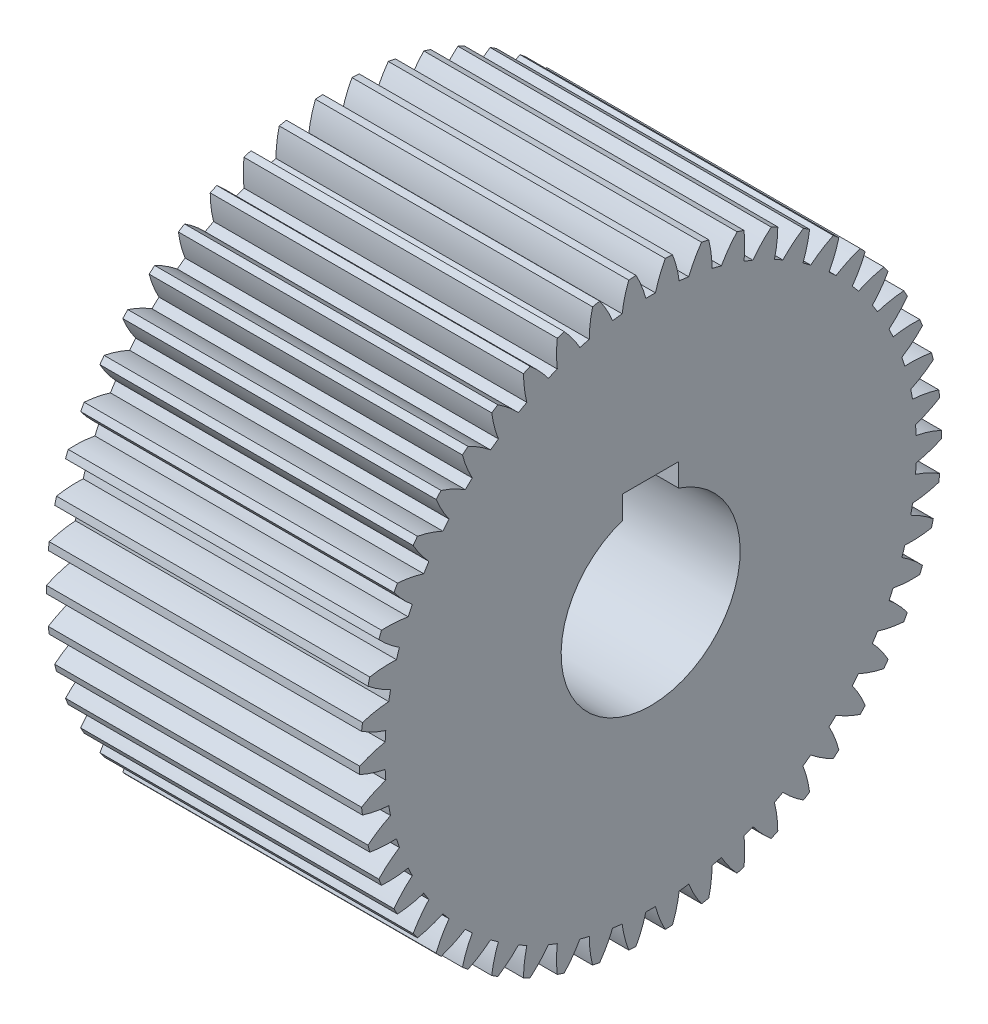
SolidWorks part; units mm, degrees
ref_plane "Plane1" through (0, 0, 0) normal (0, 0, 1) x (1, 0, 0)
ref_plane "Plane2" through (0, 0, 0) normal (0, 1, 0) x (1, 0, 0)
ref_plane "Plane3" through (0, 0, 0) normal (1, 0, 0) x (0, 0, -1)
sketch "HoldingSke" plane through (0, 0, 0) normal (0, 1, 0) x (1, 0, 0)
  line L0 (0, 0) -> (0.3214, -0.383)
  line L1 (-15, 0) -> (100, 0) construction
  line L2 (0, 0) -> (-2.1039, 2.3779)
  line L3 (0, 0) -> (-11.863, 4.5341)
  line L4 (0, 0) -> (5.5511, 6.6156)
  line L5 (0, 0) -> (-46.8476, -17.4728)
  line L6 (0, 0) -> (-46.4219, -31.321)
  line L7 (-2.1039, 2.3779) -> (9.9501, 57.0652)
  line L8 (-76.2, 54.61) -> (-72.9, 54.61)
  line L9 (-71.009, 38.7566) -> (-53.1078, 45.2721)
  line L10 (-76.2, 71.12) -> (104.1128, 71.12)
  line L11 (0, 0) -> (-56, 0)
  line L12 (-76.2, 101.6) -> (-76.133, 101.6)
  line L13 (24.9733, 27.94) -> (52.9518, 28.4284)
  line L14 (24.9733, 27.94) -> (24.9743, 27.94)
  line L15 (24.9733, 27.94) -> (100.4006, 29.5858)
  line L16 (-63.627, -2) -> (-12.827, -2)
  circle A0 centre (0, 0) radius 16
  circle A1 centre (0, 0) radius 37.5
  circle A2 centre (0, 0) radius 37.5
  circle A3 centre (0, 0) radius 16
  dimension "MHD" = 75
  dimension "Hub_dia" = 75
  dimension "Bore" = 32
  dimension "MBD" = 32
  dimension "Num_teeth" = 50
  dimension "Pitch" = 0.5
  dimension "Overall_len" = 50
  dimension "Show_teeth" = 50
  dimension "Thickness" = 56
  dimension "OAL" = 56.0001
  dimension "T_dim" = 3.3
  dimension "Ap" = 20
  dimension "H" = 19.05
  dimension "Pitch_radius" = 180.3128
  dimension "Width" = 56
  dimension "Backlash" = 0.067
  dimension "Addendum_fac" = 1
  dimension "Dedendum_fac" = 1.25
  dimension "Clearance_fac" = 0.25
  dimension "Dedendum_add" = 0.001
  dimension "Module" = 2
sketch "BasProSke" plane through (0, 0, 0) normal (0, 1, 0) x (1, 0, 0)
  line L0 (-10, 0) -> (60, 0) construction
  line L1 (0, 0) -> (0, 52)
  line L2 (0, 0) -> (56, 0)
  line L3 (56, 0) -> (56, 52)
  line L4 (56, 52) -> (0, 52)
  dimension "Thickness" = 56
  dimension "Diameter" = 104
revolve "Base-Revolve" add sketch "BasProSke" angle 360 about L0
sketch "TooCutSke" plane through (0, 0, 0) normal (1, 0, 0) x (0, 0, -1)
  line L1 (0, 0) -> (0, 107) construction
  line L2 (0, 0) -> (-1.6878, 49.9715) construction
  line L3 (0, 0) -> (-6.2764, 99.7605) construction
  line L4 (-1.6878, 49.9715) -> (-3.1382, 49.8803) construction
  arc A0 (0.8606, 47.4912) -> (-0.8606, 47.4912) centre (0, 0) ccw
  arc A1 (2.629, 51.9589) -> (-2.629, 51.9589) centre (0, 0) ccw
  circle A2 centre (0, 0) radius 50 construction
  circle A3 centre (0, 0) radius 46.9846 construction
  arc A4 (-0.8606, 47.4912) -> (-2.629, 51.9589) centre (-20.2064, 42.4176) ccw
  arc A5 (2.629, 51.9589) -> (0.8606, 47.4912) centre (20.2064, 42.4176) ccw
  dimension "Root_dia" = 94.998
  dimension "Overcut_dia" = 104.0508
  dimension "Pitch_dia" = 100
  dimension "Base_dia" = 93.9693
  dimension "Flank_rad" = 20
  dimension "Half_ang" = 3.6
  dimension "Half_CT" = 1.4533
extrude "ToothCut" cut sketch "TooCutSke" along normal through all
fillet "Breaks" [suppressed] radius 0.04
fillet "RootFillets" [suppressed] radius 0.501
pattern_circular "TeethCuts" count 50 every 7.2 about axis through (-10, 0, 0) along (1, 0, 0) of "ToothCut", "RootFillets", "Breaks"
sketch "HubNeaOneSke" plane through (0, 0, 0) normal (-1, 0, 0) x (0, 0, 1)
  circle A0 centre (0, 0) radius 37.5
  dimension "Diameter" = 75
extrude "HubNearOne" [suppressed] add sketch "HubNeaOneSke" along normal blind 12.7001
sketch "HubNeaBotSke" plane through (0, 0, 0) normal (-1, 0, 0) x (0, 0, 1)
  circle A0 centre (0, 0) radius 37.5
  dimension "Diameter" = 75
extrude "HubNearBoth" [suppressed] add sketch "HubNeaBotSke" along normal blind 6.35
ref_plane "FarPln" through (56, 0, 0) normal (1, 0, 0) x (0, 0, -1)
sketch "HubFarSke" plane through (56, 0, 0) normal (1, 0, 0) x (0, 0, -1)
  circle A0 centre (0, 0) radius 37.5
  dimension "Diameter" = 75
extrude "HubFar" [suppressed] add sketch "HubFarSke" along normal blind 6.35
sketch "BorSke" plane through (0, 0, 0) normal (1, 0, 0) x (0, 0, -1)
  circle A0 centre (0, 0) radius 16
  dimension "Diameter" = 32
extrude "Bore" cut sketch "BorSke" along normal mid plane 112.0001
sketch "KeySke" plane through (0, 0, 0) normal (1, 0, 0) x (0, 0, -1)
  line L0 (-5, 0) -> (-5, 19.3)
  line L1 (-5, 19.3) -> (5, 19.3)
  line L2 (5, 19.3) -> (5, 0)
  line L3 (0, 0) -> (0, 34) construction
  line L4 (-5, 0) -> (5, 0)
  dimension "Offset" = 19.3
  dimension "Width" = 10
extrude "Keyway" cut sketch "KeySke" along normal mid plane 112.0001
pattern_circular "Keyway2" [suppressed] count 2 every 90 about axis through (-10, 0, 0) along (1, 0, 0)
equation "' \"Module@HoldingSke\" = 6.35"
equation "' \"Num_teeth@HoldingSke\" = 12"
equation "' \"Ap@HoldingSke\" =  20"
equation "' \"Ap@HoldingSke\" = 20"
equation "' \"Width@HoldingSke\" = 0.5 * 25.4"
equation "' \"Hub_dia@HoldingSke\"= 1 * 25.4"
equation "' \"Hub_dia@HoldingSke\" = 1 * 25.4"
equation "' \"Overall_len@HoldingSke\" = 1.0 * 25.4"
equation "' \"Bore@HoldingSke\" = 0.75 * 25.4"
equation "' \"T_dim@HoldingSke\" = 0.1 * 25.4"
equation "' \"Width@KeySke\" = 0.25 * 25.4"
equation "' \"Show_teeth@HoldingSke\" = 13"
equation "' \"Backlash@HoldingSke\" = 0.009 * 25.4"
equation "' \"Addendum_fac@HoldingSke\" = 1.0"
equation "' \"Dedendum_fac@HoldingSke\" = 1.25"
equation "' \"Dedendum_add@HoldingSke\" = 0.00005 * 25.4"
equation "' \"Clearance_fac@HoldingSke\" = 0.25"
equation "\"Pitch@HoldingSke\" = 1 / \"Module@HoldingSke\""
equation "\"Overcut_dia@TooCutSke\" = (\"Num_teeth@HoldingSke\" + 2 * \"Addendum_fac@HoldingSke\") / \"Pitch@HoldingSke\" + 0.002 * 25.4"
equation "\"Pitch_dia@TooCutSke\" = \"Num_teeth@HoldingSke\" / \"Pitch@HoldingSke\""
equation "\"Base_dia@TooCutSke\" = \"Num_teeth@HoldingSke\" / \"Pitch@HoldingSke\" * cos((\"Ap@HoldingSke\"  * 3.14159265 / 180))"
equation "\"Root_dia@TooCutSke\" = (\"Num_teeth@HoldingSke\" + 2) / \"Pitch@HoldingSke\" - 2 * (\"Addendum_fac@HoldingSke\" + \"Dedendum_fac@HoldingSke\") / \"Pitch@HoldingSke\" - \"Dedendum_add@HoldingSke\" * 2"
equation "\"Half_ang@TooCutSke\" = 180 / \"Num_teeth@HoldingSke\""
equation "\"Half_CT@TooCutSke\" = \"Num_teeth@HoldingSke\" / \"Pitch@HoldingSke\" * sin((3.14159265 / 2 / \"Num_teeth@HoldingSke\")) / 2 - 7 * \"Backlash@HoldingSke\" / 4"
equation "\"Flank_rad@TooCutSke\" = \"Num_teeth@HoldingSke\" / \"Pitch@HoldingSke\" / 5"
equation "\"Radius@RootFillets\" = \"Clearance_fac@HoldingSke\" / \"Pitch@HoldingSke\" + \"Dedendum_add@HoldingSke\""
equation "\"Break_rad@Breaks\" = 0.02 / \"Pitch@HoldingSke\""
equation "\"Thickness@HoldingSke\" = \"Width@HoldingSke\""
equation "\"OAL@HoldingSke\" = \"Thickness@HoldingSke\""
equation "\"MHD@HoldingSke\" = (\"Num_teeth@HoldingSke\" + 2) / \"Pitch@HoldingSke\" - 2 * (\"Addendum_fac@HoldingSke\" + \"Dedendum_fac@HoldingSke\")  / \"Pitch@HoldingSke\" - \"Dedendum_add@HoldingSke\" * 2"
equation "\"MBD@HoldingSke\" = (\"Num_teeth@HoldingSke\" + 2) / \"Pitch@HoldingSke\" - 2 * (\"Addendum_fac@HoldingSke\" + \"Dedendum_fac@HoldingSke\")  / \"Pitch@HoldingSke\" - \"Dedendum_add@HoldingSke\" * 2 - 0.002 * 25.4"
equation "\"MHD@HoldingSke\" = ((sgn( \"MHD@HoldingSke\" - \"Hub_dia@HoldingSke\" )-1)*( \"MHD@HoldingSke\" - \"Hub_dia@HoldingSke\" ))/-2+ \"Hub_dia@HoldingSke\""
equation "\"MBD@HoldingSke\" = ((sgn( \"MBD@HoldingSke\" - \"Bore@HoldingSke\" )-1)*( \"MBD@HoldingSke\" - \"Bore@HoldingSke\" ))/-2+ \"Bore@HoldingSke\""
equation "\"OAL@HoldingSke\" = ((sgn( \"OAL@HoldingSke\" - \"Overall_len@HoldingSke\" )+1)*( \"OAL@HoldingSke\" - \"Overall_len@HoldingSke\" ))/2 + \"Overall_len@HoldingSke\" + 0.000002 * 25.4"
equation "\"Num_teeth@TeethCuts\" = int( \"Show_teeth@HoldingSke\" ) + 1"
equation "\"Num_teeth@TeethCuts\" = ((sgn( \"Num_teeth@TeethCuts\" - \"Num_teeth@HoldingSke\" )-1)*( \"Num_teeth@TeethCuts\" - \"Num_teeth@HoldingSke\" ))/-2+ \"Num_teeth@HoldingSke\""
equation "\"Num_teeth@TeethCuts\" = ((sgn( \"Num_teeth@TeethCuts\" - 2.0)+1)*( \"Num_teeth@TeethCuts\" - 2.0))/2 +2.0"
equation "\"Angle@TeethCuts\" = 360.0 / \"Num_teeth@HoldingSke\""
equation "\"Diameter@BasProSke\" = (\"Num_teeth@HoldingSke\" + 2 * \"Addendum_fac@HoldingSke\") / \"Pitch@HoldingSke\""
equation "\"Thickness@BasProSke\"  = \"Thickness@HoldingSke\""
equation "' \"Fillet_rad@BasProSke\" =  \"Thickness@HoldingSke\" * 0.05"
equation "' \"Fillet_rad@BasProSke\" = \"Thickness@HoldingSke\" * 0.05"
equation "\"MHD@HoldingSke\" = ((sgn( \"MHD@HoldingSke\" - \"Root_dia@TooCutSke\" )-1)*( \"MHD@HoldingSke\" - \"Root_dia@TooCutSke\" ))/-2+ \"Root_dia@TooCutSke\""
equation "\"Diameter@HubNeaOneSke\" = \"MHD@HoldingSke\""
equation "\"Length@HubNearOne\" = \"OAL@HoldingSke\" - \"Thickness@BasProSke\""
equation "\"Diameter@HubNeaBotSke\" = \"MHD@HoldingSke\""
equation "\"Length@HubNearBoth\" = ( \"OAL@HoldingSke\" - \"Thickness@BasProSke\" ) / 2.0"
equation "\"Thickness@FarPln\" = \"Thickness@BasProSke\""
equation "\"Diameter@HubFarSke\" = \"MHD@HoldingSke\""
equation "\"Length@HubFar\" = ( \"OAL@HoldingSke\" - \"Thickness@BasProSke\" ) / 2.0"
equation "\"Diameter@BorSke\" = \"MBD@HoldingSke\""
equation "\"D1@Bore\" = \"OAL@HoldingSke\" * 2.0"
equation "\"D1@Keyway\" = \"OAL@HoldingSke\" * 2.0"
equation "\"Offset@KeySke\" = \"T_dim@HoldingSke\" + \"MBD@HoldingSke\" / 2.0"
